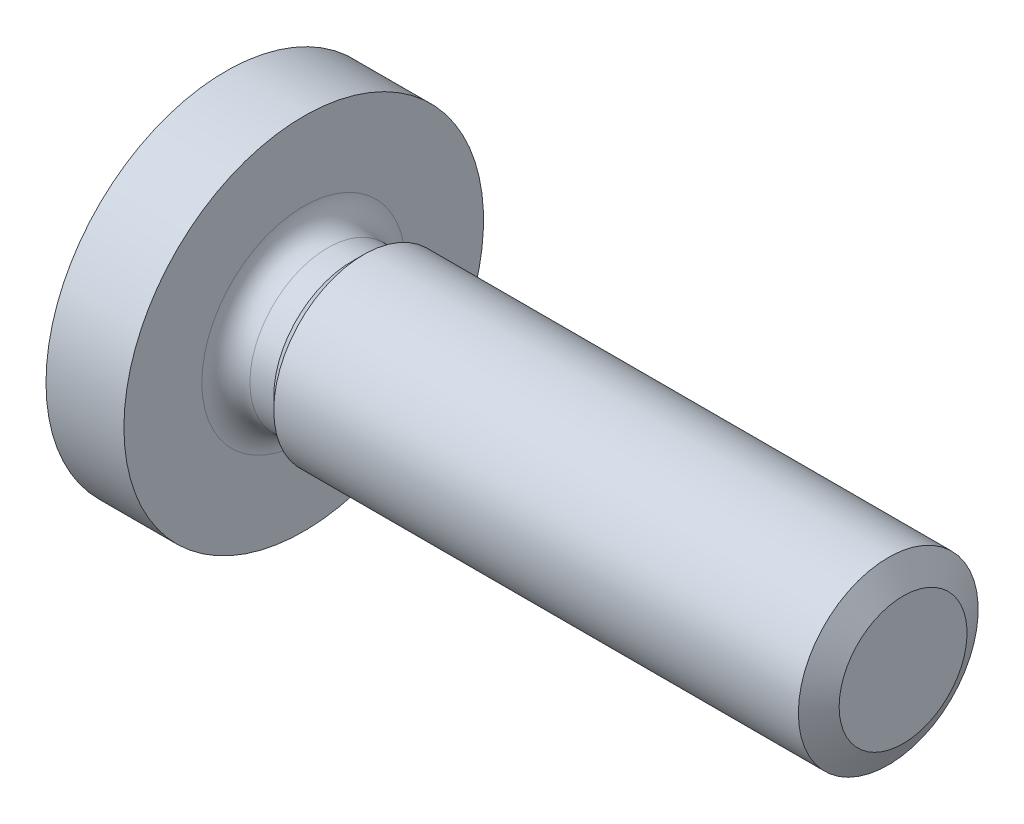
SolidWorks part; units mm, degrees
revolve "基体-旋转" add sketch "草图2" angle 360 about L0
sketch "草图2" plane through (0, 0, 0) normal (0, 0, 1) x (1, 0, 0)
  line L0 (-1.3318, 0) -> (6.5885, 0) construction
  line L1 (0, 0) -> (24.6, 0)
  line L2 (24.6, 0) -> (24.6, 3)
  line L3 (24.6, 3) -> (6.6, 3)
  line L4 (6.6, 3) -> (6.198, 2.598)
  line L5 (6.198, 2.598) -> (5.402, 2.598)
  line L6 (4.6, 3.4) -> (4.6, 6)
  line L7 (4.6, 6) -> (2, 6)
  arc A0 (4.6, 3.4) -> (5.402, 2.598) centre (5.402, 3.4) ccw
  arc A1 (0, 0) -> (2, 6) centre (10, 0) cw
  dimension "D3" = 10
  dimension "dk" = 12
  dimension "d" = 6
  dimension "l" = 20
  dimension "a" = 2
  dimension "D1" = 45
  dimension "D2" = 5.196
  dimension "da" = 6.8
  dimension "k" = 4.6
cosmetic thread "装饰螺纹线1" parameters "D1"=18, "D2"=5.196
material "钢"
ref_plane "前视" through (0, 0, 0) normal (0, 0, 1) x (1, 0, 0)
ref_plane "上视" through (0, 0, 0) normal (0, 1, 0) x (1, 0, 0)
ref_plane "右视" through (0, 0, 0) normal (1, 0, 0) x (0, 0, -1)
sketch "尺寸草图" plane through (0, 0, 0) normal (0, 0, 1) x (1, 0, 0)
  line L0 (0, 0) -> (20, 0)
  line L1 (0, 0) -> (0, 12)
  line L2 (20, 0) -> (20, 6.8)
  point P5 (0, 6)
  point P6 (19, 0)
  point P7 (2, 0)
  point P8 (4.6, 0)
  point P9 (10, 0)
  point P10 (6.9, 0)
  point P11 (16.4, 0)
  dimension "dk" = 12
  dimension "d" = 6
  dimension "l" = 20
  dimension "a" = 2
  dimension "da" = 6.8
  dimension "k" = 4.6
  dimension "P" = 1
  dimension "rf" = 10
  dimension "m" = 6.9
  dimension "h" = 3.6
sketch "草图3" plane through (0, 0, 0) normal (0, 0, 1) x (1, 0, 0)
  line L0 (24.1054, 3) -> (25.1054, 3)
  line L1 (25.1054, 3) -> (24.6, 2.134)
  line L2 (24.6, 2.134) -> (24.1054, 3)
  line L3 (24.6, 3) -> (6.6, 3) construction
  line L4 (24.6, -3) -> (24.6, 3) construction
  line L5 (-0.2428, 0) -> (7.1644, 0) construction
  line L6 (-1.3318, 0) -> (6.5885, 0) construction
  dimension "P" = 1
  dimension "D1" = 0.866
  dimension "D2" = 60
revolve "切除-旋转1" cut sketch "草图3" angle 360 about L5
sketch "草图5" plane through (0, 0, 0) normal (1, 0, 0) x (0, 0, -1)
  line L1 (0.5, 3.45) -> (-0.5, 3.45)
  line L2 (0.5, 3.45) -> (0.5, -3.45)
  line L3 (0.5, -3.45) -> (-0.5, -3.45)
  line L4 (-0.5, 3.45) -> (-0.5, -3.45)
  point P4 (0.5, 0)
  point P5 (0, 3.45)
  dimension "m" = 6.9
  dimension "D1" = 1
ref_plane "基准面1" through (3.6, 0, 0) normal (1, 0, 0) x (0, 0, -1)
pattern_linear "阵列(线性)1" [suppressed] count 19 spacing 1 along (1, 0, 0)
sketch "草图6" plane through (3.6, 0, 0) normal (1, 0, 0) x (0, 0, -1)
  point P0 (0, 0)
loft "切除-放样1" cut profiles "草图6", "草图5"
ref_plane "基准面2" through (0, 0, 0) normal (0, -0.7071, 0.7071) x (1, 0, 0)
mirror "镜向1" about plane through (0, 0, 0) normal (0, -0.7071, 0.7071) of "切除-放样1"
equation "\"l@草图2\" = \"l@尺寸草图\""
equation "\"dk@草图2\" = \"dk@尺寸草图\""
equation "\"k@草图2\" = \"k@尺寸草图\""
equation "\"D2@草图2\" = \"d@尺寸草图\"*0.866"
equation "\"a@草图2\" = \"a@尺寸草图\""
equation "\"D3@草图2\" = \"rf@尺寸草图\""
equation "\"d@草图2\" = \"d@尺寸草图\""
equation "\"da@草图2\" = \"da@尺寸草图\""
equation "\"D2@装饰螺纹线1\" = \"d@尺寸草图\"*0.866"
equation "\"D1@装饰螺纹线1\" = \"l@尺寸草图\"-\"a@尺寸草图\""
equation "\"P@草图3\" = \"P@尺寸草图\""
equation "\"D1@草图3\" = \"P@尺寸草图\"*0.866"
equation "\"h@基准面1\" = \"h@尺寸草图\""
equation "\"D1@草图5\" = \"P@尺寸草图\""
equation "\"m@草图5\" = \"m@尺寸草图\""
equation "\"D3@阵列(线性)1\" = \"P@尺寸草图\""
equation "\"D1@阵列(线性)1\" = (\"l@尺寸草图\"-\"a@尺寸草图\")/\"P@尺寸草图\"+1"
